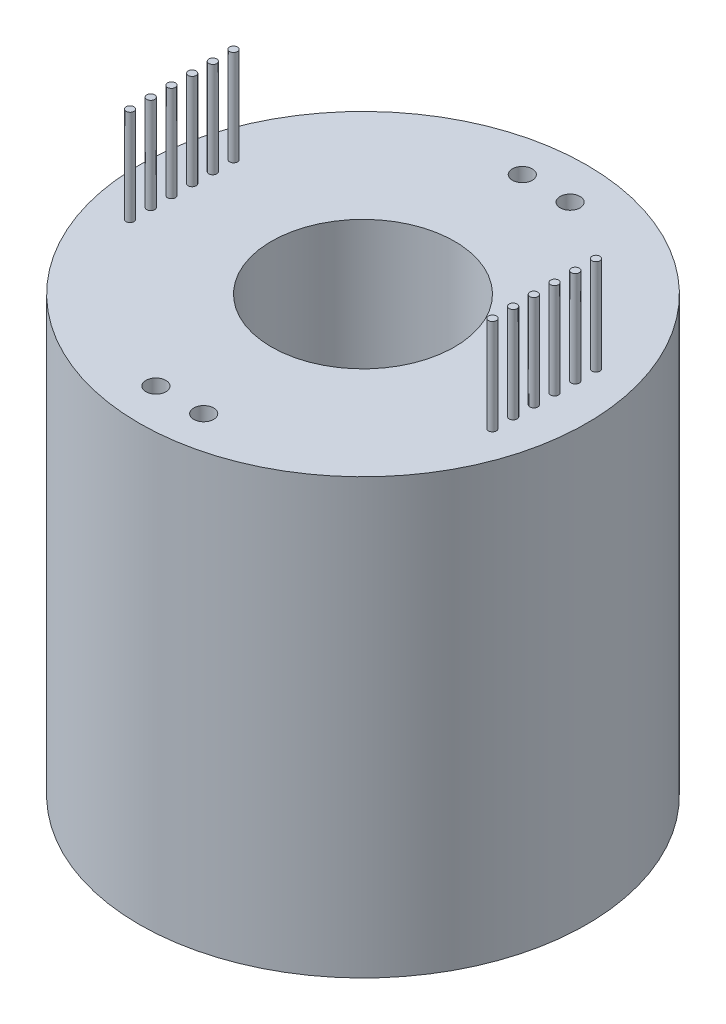
SolidWorks part; units mm, degrees
ref_plane "Front Plane" through (0, 0, 0) normal (0, 0, 1) x (1, 0, 0)
ref_plane "Top Plane" through (0, 0, 0) normal (0, 1, 0) x (1, 0, 0)
ref_plane "Right Plane" through (0, 0, 0) normal (1, 0, 0) x (0, 0, -1)
sketch "Sketch1" plane through (0, 0, 0) normal (0, 0, 1) x (1, 0, 0)
  line L0 (0, 0) -> (0, 54.5) construction
  line L1 (0, 54.5) -> (28.09, 54.5)
  line L2 (28.09, 54.5) -> (28.09, 0)
  line L3 (28.09, 0) -> (0, 0)
  line L4 (0, 0) -> (0, 54.5)
  dimension "D1" = 56.18
  dimension "D2" = 54.5
revolve "Revolve1" add sketch "Sketch1" angle 360 about L0
hole_wizard "1/4 NPT Tapped Hole1" positions "Sketch2" profile "Sketch3" size "1/4" standard "ANSI Inch" end condition through all
sketch "Sketch2" plane through (0, 54.5, 0) normal (0, 1, 0) x (1, 0, 0)
  point P0 (0, 0)
sketch "Sketch3" plane through (0, 54.5, 0) normal (1, 0, 0) x (0, 0, 1)
  line L0 (0, 0) -> (0, 54.5)
  line L1 (0, 54.5) -> (5.5626, 54.5)
  line L2 (-6.558, 10.0203) -> (-6.858, 0) construction
  line L3 (5.5626, 54.5) -> (5.5626, 10.0203)
  line L4 (5.5626, 10.0203) -> (6.558, 10.0203)
  line L5 (6.558, 10.0203) -> (6.858, 0)
  line L7 (6.858, 0) -> (0, 0)
  line L8 (0, -6.35) -> (0, 107.95) construction
  line L11 (-5.5626, 10.0203) -> (-6.558, 10.0203) construction
  dimension "Thru Tap Drill Dia." = 11.1252
  dimension "Thru Tap Drill Depth" = 54.5
  dimension "Thread Dia." = 13.716
  dimension "Thread Angle" = 3.43
  dimension "Thread Depth" = 10.0203
hole_wizard "M3x0.5 Tapped Hole1" positions "Sketch4" profile "Sketch5" tap size "M3x0.5" standard "ANSI Metric"
sketch "Sketch4" plane through (0, 54.5, 0) normal (0, 1, 0) x (1, 0, 0)
  line L0 (0, 0) -> (0, 23) construction
  line L1 (0, 0) -> (0, -23) construction
  line L2 (3, -23) -> (0, -23) construction
  line L3 (0, -23) -> (-3, -23) construction
  line L5 (3, 23) -> (0, 23) construction
  line L6 (0, 23) -> (-3, 23) construction
  point P0 (-3, 23)
  point P11 (3, -23)
  point P14 (-3, -23)
  point P17 (3, 23)
  dimension "D1" = 46
  dimension "D2" = 6
sketch "Sketch5" plane through (-3, 54.5, -23) normal (1, 0, 0) x (0, 0, 1)
  line L0 (0, 0) -> (0, 5.7511)
  line L1 (0, 5.7511) -> (1.25, 5)
  line L2 (1.25, 5) -> (1.25, 0)
  line L5 (1.25, 0) -> (0, 0)
  line L10 (0, 5.7511) -> (-1.25, 5) construction
  line L11 (0, -6.35) -> (0, 107.95) construction
  dimension "Tap Drill Dia." = 2.5
  dimension "Tap Drill Depth" = 5
  dimension "Drill Angle" = 118
cosmetic thread "Hole Thread1" parameters "D1"=5, "D2"=3
cosmetic thread "Hole Thread2" parameters "D1"=5, "D2"=3
cosmetic thread "Hole Thread3" parameters "D1"=5, "D2"=3
cosmetic thread "Hole Thread4" parameters "D1"=5, "D2"=3
sketch "Sketch6" plane through (0, 54.5, 0) normal (0, 1, 0) x (1, 0, 0)
  line L0 (-22.75, 6.5) -> (-22.75, 3.9) construction
  line L1 (-22.75, 3.9) -> (-22.75, 1.3) construction
  line L2 (-22.75, 1.3) -> (-22.75, -1.3) construction
  line L3 (-22.75, -1.3) -> (-22.75, -3.9) construction
  line L4 (-22.75, -3.9) -> (-22.75, -6.5) construction
  line L5 (-22.75, 0) -> (0, 0) construction
  line L6 (0, 28.09) -> (0, -28.09) construction
  circle A0 centre (-22.75, 6.5) radius 0.5
  circle A1 centre (-22.75, 3.9) radius 0.5
  circle A2 centre (-22.75, 1.3) radius 0.5
  circle A3 centre (-22.75, -1.3) radius 0.5
  circle A4 centre (-22.75, -3.9) radius 0.5
  circle A5 centre (-22.75, -6.5) radius 0.5
  circle A6 centre (0, 0) radius 28.09 construction
  circle A7 centre (22.75, -6.5) radius 0.5
  circle A8 centre (22.75, -3.9) radius 0.5
  circle A9 centre (22.75, -1.3) radius 0.5
  circle A10 centre (22.75, 1.3) radius 0.5
  circle A11 centre (22.75, 3.9) radius 0.5
  circle A12 centre (22.75, 6.5) radius 0.5
  point P20 (0, 0)
  dimension "D1" = 1
  dimension "D2" = 22.75
  dimension "D3" = 13
extrude "Boss-Extrude1" add sketch "Sketch6" along normal blind 12 separate body
sketch "Sketch7" plane through (0, 54.5, 0) normal (0, 1, 0) x (1, 0, 0)
  circle A0 centre (0, 0) radius 10.325
  dimension "D1" = 20.65
split line "Split Line2"
sketch "Sketch8" plane through (0, 54.5, 0) normal (0, 1, 0) x (1, 0, 0)
  circle A0 centre (0, 0) radius 11.5
  dimension "D1" = 23
extrude "Cut-Extrude1" cut sketch "Sketch8" against normal through all
